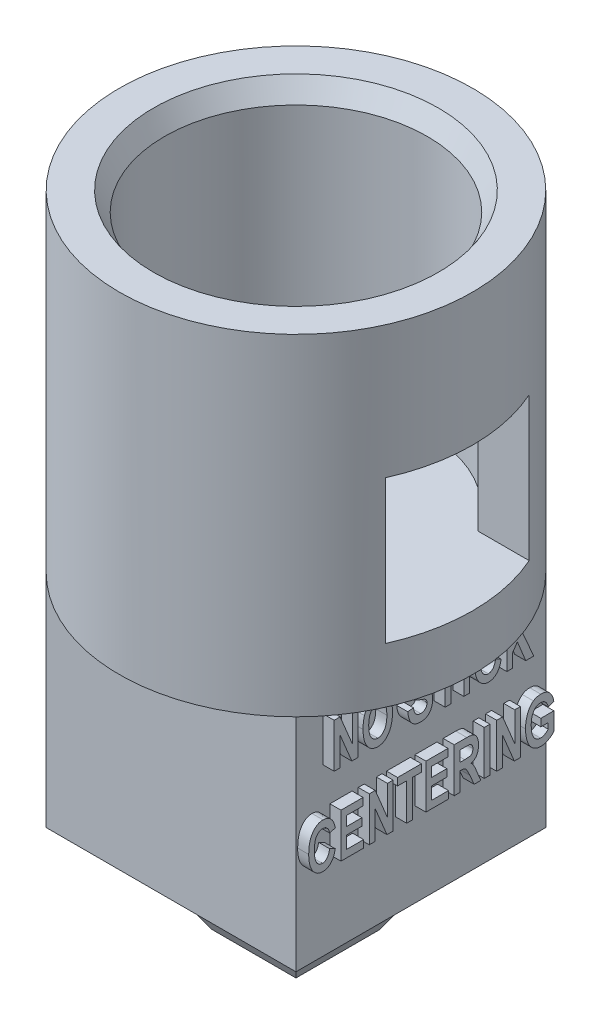
SolidWorks part; units mm, degrees
ref_plane "Спереди" through (0, 0, 0) normal (0, 0, 1) x (1, 0, 0)
ref_plane "Сверху" through (0, 0, 0) normal (0, 1, 0) x (1, 0, 0)
ref_plane "Справа" through (0, 0, 0) normal (1, 0, 0) x (0, 0, -1)
sketch "Sketch1" plane through (0, 0, 0) normal (0, 1, 0) x (1, 0, 0)
  line L1 (4.8, -4.8) -> (-4.8, -4.8)
  line L2 (4.8, -4.8) -> (4.8, 4.8)
  line L3 (4.8, 4.8) -> (-4.8, 4.8)
  line L4 (-4.8, -4.8) -> (-4.8, 4.8)
  line L5 (4.8, -4.8) -> (-4.8, 4.8) construction
  line L6 (4.8, 4.8) -> (-4.8, -4.8) construction
  point P0 (0, 0)
  dimension "D1" = 9.6
extrude "Boss-Extrude1" add sketch "Sketch1" along normal blind 28
sketch "Sketch2" plane through (0, 28, 0) normal (0, 1, 0) x (1, 0, 0)
  circle A0 centre (0, 0) radius 16
  dimension "D1" = 32
extrude "Boss-Extrude2" add sketch "Sketch2" along normal blind 30
sketch "Sketch3" plane through (0, 58, 0) normal (0, 1, 0) x (1, 0, 0)
  circle A0 centre (0, 0) radius 11.9
  dimension "D1" = 23.8
extrude "Cut-Extrude1" cut sketch "Sketch3" against normal blind 25
chamfer "Chamfer1" distance 1 angle 60 4 edges at (4.8, 0, 0) (0, 0, -4.8) (-4.8, 0, 0) (0, 0, 4.8)
chamfer "Chamfer2" distance 1 angle 60 1 edges at (0, 58, 11.9)
sketch "Sketch4" plane through (0, 28, 0) normal (0, -1, 0) x (1, 0, 0)
  line L1 (-11.3137, 11.3137) -> (11.3137, 11.3137)
  line L2 (-11.3137, 11.3137) -> (-11.3137, -11.3137)
  line L3 (-11.3137, -11.3137) -> (11.3137, -11.3137)
  line L4 (11.3137, 11.3137) -> (11.3137, -11.3137)
  line L5 (-11.3137, 11.3137) -> (11.3137, -11.3137) construction
  line L6 (-11.3137, -11.3137) -> (11.3137, 11.3137) construction
  line L7 (-7.75, 7.75) -> (7.75, 7.75)
  line L8 (-7.75, 7.75) -> (-7.75, -7.75)
  line L9 (-7.75, -7.75) -> (7.75, -7.75)
  line L10 (7.75, 7.75) -> (7.75, -7.75)
  line L11 (-7.75, 7.75) -> (7.75, -7.75) construction
  line L12 (-7.75, -7.75) -> (7.75, 7.75) construction
  circle A0 centre (0, 0) radius 16 construction
  point P0 (0, 0)
  point P9 (0, 0)
  dimension "D1" = 15.5
extrude "Boss-Extrude3" add sketch "Sketch4" along normal blind 20
sketch "Sketch6" plane through (-11.3137, 0, 0) normal (-1, 0, 0) x (0, 0, 1)
  line L0 (-11.3137, 23) -> (11.3137, 23) construction
  line L1 (-11.3137, 8) -> (-11.3137, 28) construction
  line L2 (11.3137, 8) -> (11.3137, 28) construction
  line L3 (11.3137, 28) -> (-11.3137, 28) construction
  text T0 "REMOVE\r\n  AFTER\r\n  FLIGHT" font "Arial" height 4
  dimension "D1" = 5
extrude "Boss-Extrude4" add sketch "Sketch6" along normal blind 1
sketch "Sketch7" plane through (11.3137, 0, 0) normal (1, 0, 0) x (0, 0, -1)
  line L0 (-11.3137, 23) -> (11.3137, 23) construction
  line L1 (-11.3137, 8) -> (-11.3137, 28) construction
  line L2 (11.3137, 8) -> (11.3137, 28) construction
  line L3 (11.3137, 28) -> (-11.3137, 28) construction
  text T0 "<b>  NO STICK</b>\r\n<b>CENTERING</b>" font "Arial" height 4
  dimension "D1" = 5
extrude "Boss-Extrude5" add sketch "Sketch7" along normal blind 1
sketch "Sketch8" plane through (0, 33, 0) normal (0, 1, 0) x (1, 0, 0)
  line L0 (11.9, 0) -> (-11.9, 0) construction
  line L2 (5.4, -6.5) -> (18.4, -6.5)
  line L3 (5.4, -6.5) -> (5.4, 6.5)
  line L4 (5.4, 6.5) -> (18.4, 6.5)
  line L5 (18.4, -6.5) -> (18.4, 6.5)
  line L6 (5.4, -6.5) -> (18.4, 6.5) construction
  line L7 (5.4, 6.5) -> (18.4, -6.5) construction
  circle A2 centre (0, 0) radius 11.9 construction
  point P9 (11.9, 0)
  dimension "D1" = 13
extrude "Cut-Extrude2" cut sketch "Sketch8" along normal blind 13
chamfer "Chamfer3" distance 4 angle 50 1 edges at (11.9, 46, 0)
